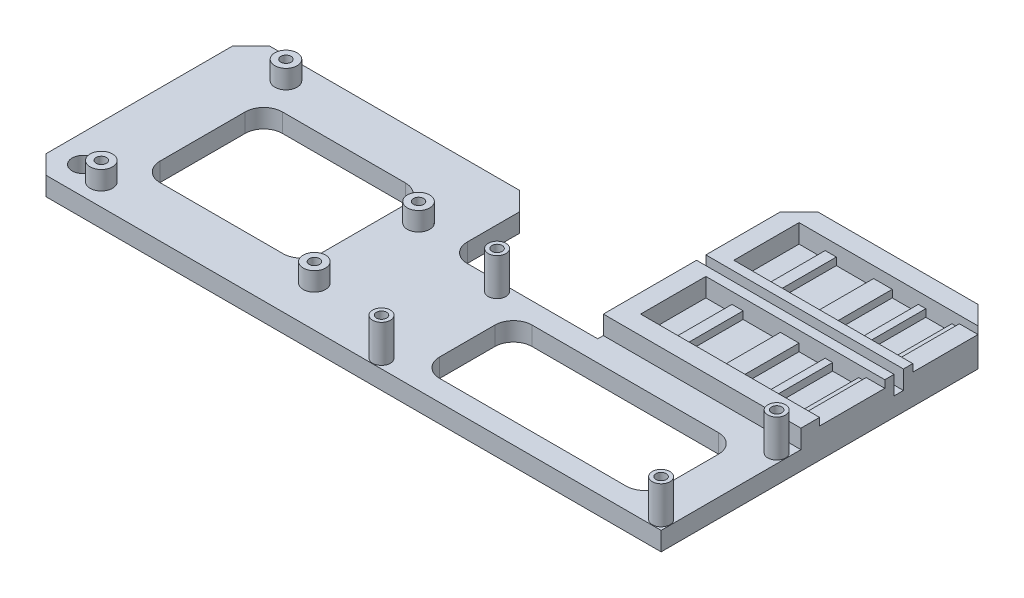
SolidWorks part; units mm, degrees
material "ABS"
ref_plane "Front Plane" through (0, 0, 0) normal (0, 0, 1) x (1, 0, 0)
ref_plane "Top Plane" through (0, 0, 0) normal (0, 1, 0) x (1, 0, 0)
ref_plane "Right Plane" through (0, 0, 0) normal (1, 0, 0) x (0, 0, -1)
sketch "Sketch1" plane through (0, 0, 0) normal (0, 1, 0) x (1, 0, 0)
  line L1 (-85, 30) -> (85, 30)
  line L2 (-85, 30) -> (-85, -30)
  line L3 (-85, -30) -> (85, -30)
  line L4 (85, 30) -> (85, -30)
  line L5 (-85, 30) -> (85, -30) construction
  line L6 (-85, -30) -> (85, 30) construction
  line L7 (85, 30) -> (32, 30)
  line L8 (85, 30) -> (85, 60)
  line L9 (85, 60) -> (32, 60)
  line L10 (32, 30) -> (32, 60)
  point P0 (0, 0)
  dimension "D1" = 170
  dimension "D2" = 60
  dimension "D3" = 90
  dimension "D4" = 53
extrude "Boss-Extrude1" add sketch "Sketch1" along normal blind 5 contours L4 L1 L2 L3 | L10 L1 L8 L9
sketch "Sketch3" plane through (0, 5, 0) normal (0, 1, 0) x (1, 0, 0)
  line L1 (32, 30) -> (-8, 30)
  line L2 (32, 30) -> (32, 6)
  line L3 (32, 6) -> (-8, 6)
  line L4 (-8, 30) -> (-8, 6)
  dimension "D1" = 40
  dimension "D2" = 24
extrude "Cut-Extrude1" cut sketch "Sketch3" against normal blind 5
sketch "Sketch5" plane through (0, 0, 0) normal (0, -1, 0) x (1, 0, 0)
  circle A0 centre (-77.5, 22.5) radius 3
extrude "Cut-Extrude2" cut sketch "Sketch5" against normal blind 10
sketch "Sketch6" plane through (0, 5, 0) normal (0, 1, 0) x (1, 0, 0)
  circle A0 centre (-71.03, -24.13) radius 3
  circle A1 centre (-69.76, 24.13) radius 3
  circle A2 centre (-18.96, -19.05) radius 3
  circle A3 centre (-18.96, 8.89) radius 3
  circle A4 centre (-69.76, 24.13) radius 1.375
  circle A5 centre (-18.96, 8.89) radius 1.375
  circle A6 centre (-18.96, -19.05) radius 1.375
  circle A7 centre (-71.03, -24.13) radius 1.375
  dimension "D1" = 6
  dimension "D2" = 2.75
sketch "Sketch7" plane through (0, 5, 0) normal (0, 1, 0) x (1, 0, 0)
  line L0 (-8, 6) -> (32, 6) construction
  line L1 (5, -30) -> (85, -30)
  line L2 (5, -30) -> (5, 6)
  line L3 (5, 6) -> (85, 6)
  line L4 (85, -30) -> (85, 6)
  line L5 (5, -30) -> (85, 6) construction
  line L6 (5, 6) -> (85, -30) construction
  line L7 (7.5, 3.5) -> (82.5, 3.5)
  line L8 (7.5, 3.5) -> (7.5, -27.5)
  line L9 (7.5, -27.5) -> (82.5, -27.5)
  line L10 (82.5, 3.5) -> (82.5, -27.5)
  line L11 (7.5, 3.5) -> (82.5, -27.5) construction
  line L12 (7.5, -27.5) -> (82.5, 3.5) construction
  line L13 (85, 60) -> (85, -30) construction
  point P0 (45, -12)
  point P5 (45, -12)
  dimension "D1" = 80
  dimension "D2" = 36
  dimension "D3" = 0
  dimension "D4" = 75
  dimension "D5" = 31
extrude "Boss-Extrude2" add sketch "Sketch6" along normal blind 5
sketch "Sketch8" plane through (0, 5, 0) normal (0, 1, 0) x (1, 0, 0)
  circle A0 centre (7.5, 3.5) radius 2.375
  circle A1 centre (7.5, -27.5) radius 2.375
  circle A2 centre (82.5, -27.5) radius 2.375
  circle A3 centre (82.5, 3.5) radius 2.375
  circle A4 centre (7.5, 3.5) radius 1.375
  circle A5 centre (7.5, -27.5) radius 1.375
  circle A6 centre (82.5, -27.5) radius 1.375
  circle A7 centre (82.5, 3.5) radius 1.375
  dimension "D1" = 2.75
  dimension "D2" = 4.75
extrude "Boss-Extrude3" add sketch "Sketch8" along normal blind 10
sketch "Sketch9" plane through (0, 5, 0) normal (0, 1, 0) x (1, 0, 0)
  line L0 (85, 60) -> (32, 60)
  line L1 (80, 55) -> (37, 55)
  line L2 (80, 55) -> (80, 37.5)
  line L3 (80, 37.5) -> (37, 37.5)
  line L4 (37, 55) -> (37, 37.5)
  line L5 (80, 30) -> (37, 30)
  line L6 (80, 30) -> (80, 12.5)
  line L7 (80, 12.5) -> (37, 12.5)
  line L8 (37, 30) -> (37, 12.5)
  line L9 (32, 60) -> (32, 32.5)
  line L10 (85, 32.5) -> (32, 32.5)
  line L11 (85, 60) -> (85, 32.5)
  line L12 (85, 35) -> (32, 35)
  line L13 (32, 35) -> (32, 7.5)
  line L14 (85, 7.5) -> (32, 7.5)
  line L15 (85, 35) -> (85, 7.5)
  line M2 (32, 60) -> (32, 6)
  line M8 (85, -30) -> (85, 60)
  line M9 (85, 60) -> (32, 60)
  dimension "D1" = 5
extrude "Boss-Extrude4" add sketch "Sketch9" along normal blind 5 contours L12 L11 L4 L1 L2 L3 M9 M2 | L14 L10 L8 L5 L6 L7 M8 M2
sketch "Sketch10" plane through (0, 5, 0) normal (0, 1, 0) x (1, 0, 0)
  line L0 (80, 30) -> (37, 30) construction
  line L1 (47, 30) -> (44, 30)
  line L2 (47, 30) -> (47, 12.5)
  line L3 (47, 12.5) -> (44, 12.5)
  line L4 (44, 30) -> (44, 12.5)
  line L5 (80, 12.5) -> (37, 12.5) construction
  line L6 (37, 30) -> (37, 12.5) construction
  line L7 (80, 55) -> (37, 55) construction
  line L8 (57, 12.5) -> (62, 12.5)
  line L9 (57, 12.5) -> (57, 30)
  line L10 (57, 30) -> (62, 30)
  line L11 (62, 12.5) -> (62, 30)
  line L12 (71, 30) -> (69, 30)
  line L13 (71, 30) -> (71, 12.5)
  line L14 (71, 12.5) -> (69, 12.5)
  line L15 (69, 30) -> (69, 12.5)
  line L16 (44, 55) -> (47, 55)
  line L17 (44, 55) -> (44, 37.5)
  line L18 (44, 37.5) -> (47, 37.5)
  line L19 (47, 55) -> (47, 37.5)
  line L20 (80, 37.5) -> (37, 37.5) construction
  line L21 (80, 55) -> (37, 55) construction
  line L22 (57, 55) -> (62, 55)
  line L23 (57, 55) -> (57, 37.5)
  line L24 (57, 37.5) -> (62, 37.5)
  line L25 (62, 55) -> (62, 37.5)
  line L26 (80, 37.5) -> (37, 37.5) construction
  line L27 (69, 55) -> (71, 55)
  line L28 (69, 55) -> (69, 37.5)
  line L29 (69, 37.5) -> (71, 37.5)
  line L30 (71, 55) -> (71, 37.5)
  line L31 (80, 12.5) -> (37, 12.5) construction
  line L32 (80, 30) -> (78, 30)
  line L33 (80, 30) -> (80, 12.5)
  line L34 (80, 12.5) -> (78, 12.5)
  line L35 (78, 30) -> (78, 12.5)
  line L37 (80, 55) -> (78, 55)
  line L38 (80, 55) -> (80, 37.5)
  line L39 (80, 37.5) -> (78, 37.5)
  line L40 (78, 55) -> (78, 37.5)
  dimension "D1" = 3
  dimension "D2" = 7
  dimension "D3" = 20
  dimension "D4" = 5
  dimension "D5" = 32
  dimension "D6" = 34
  dimension "D7" = 2
extrude "Boss-Extrude5" add sketch "Sketch10" along normal blind 2
sketch "Sketch11" plane through (0, 10, 0) normal (0, 1, 0) x (1, 0, 0)
  line L0 (85, 7.5) -> (85, 32.5) construction
  line L1 (80, 30) -> (85, 30)
  line L2 (80, 30) -> (80, 12.5)
  line L3 (80, 12.5) -> (85, 12.5)
  line L4 (85, 30) -> (85, 12.5)
  line L5 (85, 35) -> (85, 60) construction
  line L6 (80, 55) -> (85, 55)
  line L7 (80, 55) -> (80, 37.5)
  line L8 (80, 37.5) -> (85, 37.5)
  line L9 (85, 55) -> (85, 37.5)
  line L10 (80, 37.5) -> (37, 37.5) construction
  line L11 (80, 12.5) -> (37, 12.5) construction
extrude "Cut-Extrude5" cut sketch "Sketch11" against normal blind 2
chamfer "Chamfer1" distance 5 angle 45 5 edges at (-85, 2.5, 30) (-85, 2.5, -30) (-8, 2.5, -30) (32, 5, -60) (85, 5, -60)
fillet "Fillet1" radius 5 1 edges at (-8, 2.5, -6)
sketch "Sketch12" plane through (0, 5, 0) normal (0, 1, 0) x (1, 0, 0)
  line L0 (-10.5, 27.5) -> (-82.5, -27.5) construction
  line L1 (-8, 25) -> (-13, 30) construction
  line L2 (-85, -25) -> (-80, -30) construction
  line L3 (7.5, 3.5) -> (82.5, -27.5) construction
  line L4 (-68, -16.4236) -> (-25, -16.4236)
  line L5 (-68, -16.4236) -> (-68, 16.4236)
  line L6 (-68, 16.4236) -> (-25, 16.4236)
  line L7 (-25, -16.4236) -> (-25, 16.4236)
  line L8 (-68, -16.4236) -> (-25, 16.4236) construction
  line L9 (-68, 16.4236) -> (-25, -16.4236) construction
  line L11 (15, 0.4) -> (75, 0.4)
  line L12 (15, 0.4) -> (15, -24.4)
  line L13 (15, -24.4) -> (75, -24.4)
  line L14 (75, 0.4) -> (75, -24.4)
  line L15 (15, 0.4) -> (75, -24.4) construction
  line L16 (15, -24.4) -> (75, 0.4) construction
  point P6 (-46.5, 0)
  point P15 (45, -12)
  dimension "D1" = 43
  dimension "D2" = 60
extrude "Cut-Extrude6" cut sketch "Sketch12" against normal through all
fillet "Fillet2" radius 5 8 edges at (75, 2.5, 24.4) (75, 2.5, -0.4) (15, 2.5, 24.4) (15, 2.5, -0.4) (-25, 2.5, 16.4236) (-68, 2.5, 16.4236) (-68, 2.5, -16.4236) (-25, 2.5, -16.4236)
hole_wizard "Ø2.8 (2.8) Diameter Hole1" positions "Sketch15" profile "Sketch14" hole size "Ø2.8" standard "ISO"
sketch "Sketch15" plane through (0, 5, 0) normal (0, 1, 0) x (1, 0, 0)
  point P0 (-69.76, 24.13)
  point P3 (-18.96, 8.89)
  point P6 (7.5, 3.5)
  point P9 (-71.03, -24.13)
  point P12 (-18.96, -19.05)
  point P15 (7.5, -27.5)
  point P18 (82.5, -27.5)
  point P21 (82.5, 3.5)
sketch "Sketch14" plane through (-69.76, 5, -24.13) normal (1, 0, 0) x (0, 0, 1)
  line L0 (0, 0) -> (0, 10.8412)
  line L1 (0, 10.8412) -> (1.4, 10)
  line L2 (1.4, 10) -> (1.4, 0)
  line L5 (1.4, 0) -> (0, 0)
  line L10 (0, 10.8412) -> (-1.4, 10) construction
  line L11 (0, -6.35) -> (0, 107.95) construction
  dimension "Hole Dia." = 2.8
  dimension "Hole Depth" = 10
  dimension "Drill Angle" = 118
